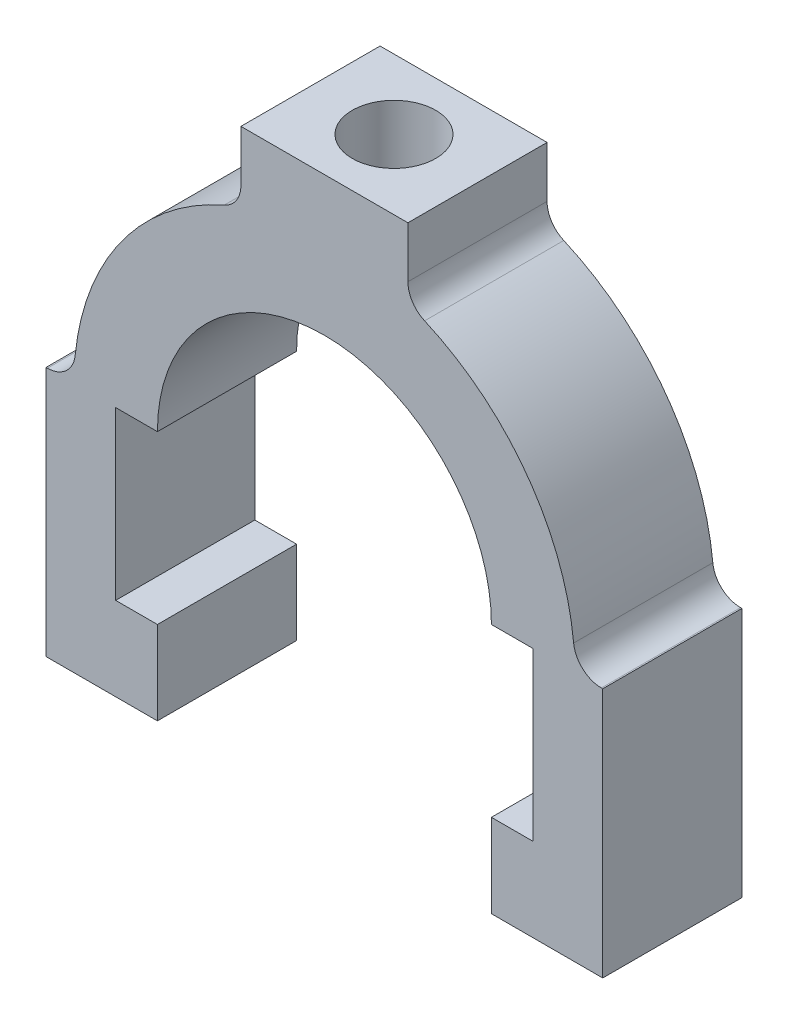
SolidWorks part; units mm, degrees
material "1060 Alloy"
ref_plane "Front Plane" through (0, 0, 0) normal (0, 0, 1) x (1, 0, 0)
ref_plane "Top Plane" through (0, 0, 0) normal (0, 1, 0) x (1, 0, 0)
ref_plane "Right Plane" through (0, 0, 0) normal (1, 0, 0) x (0, 0, -1)
sketch "Sketch1" plane through (0, 0, 0) normal (0, 0, 1) x (1, 0, 0)
  line L0 (0, 0) -> (0, 36)
  line L1 (0, 0) -> (-16, 0)
  line L2 (-16, 0) -> (-16, 12)
  line L3 (-16, 12) -> (-10, 12)
  line L4 (-10, 12) -> (-10, 36)
  line L5 (-10, 36) -> (0, 36)
  line L6 (-10, 36) -> (-16, 36)
  line L9 (-52, 80) -> (-28, 80)
  line L10 (-28, 80) -> (-28, 69.9411)
  line L11 (-52, 80) -> (-52, 69.9411)
  line L12 (-70, 36) -> (-64, 36)
  line L13 (-70, 36) -> (-80, 36)
  line L14 (-70, 12) -> (-70, 36)
  line L15 (-64, 12) -> (-70, 12)
  line L16 (-64, 0) -> (-64, 12)
  line L17 (-80, 0) -> (-64, 0)
  line L18 (-80, 0) -> (-80, 36)
  arc A0 (-64, 36) -> (-16, 36) centre (-40, 36) cw
  arc A1 (-4, 36) -> (-76, 36) centre (-40, 36) ccw
  dimension "D5" = 80
  dimension "D6" = 6
  dimension "D1" = 10
  dimension "D2" = 12
  dimension "D3" = 36
  dimension "D4" = 24
  dimension "D7" = 6
extrude "Boss-Extrude3" add sketch "Sketch1" along normal mid plane 20 contours L5 A1 L13 L12 A0 L6 | L18 L17 L16 L15 L14 L13 | A1 L10 L9 L11 | L5 L4 L3 L2 L1 L0
fillet "Fillet1" radius 4 1 edges at (-28, 69.9411, 0)
fillet "Fillet2" radius 4 1 edges at (-4, 36, 0)
fillet "Fillet3" radius 4 2 edges at (-76, 36, 0) (-52, 69.9411, 0)
sketch "Sketch3" plane through (0, 80, 0) normal (0, 1, 0) x (1, 0, 0)
  line L0 (-52, 10) -> (-28, 10) construction
  line L1 (-52, 10) -> (-52, -10) construction
  circle A0 centre (-40, 0) radius 6
  point P4 (0, 0)
  dimension "D1" = 10
  dimension "D2" = 12
extrude "Cut-Extrude2" cut sketch "Sketch3" against normal through all
ref_plane "Plane1" through (-10, 36, 10) normal (0, 1, 0) x (1, 0, 0)
